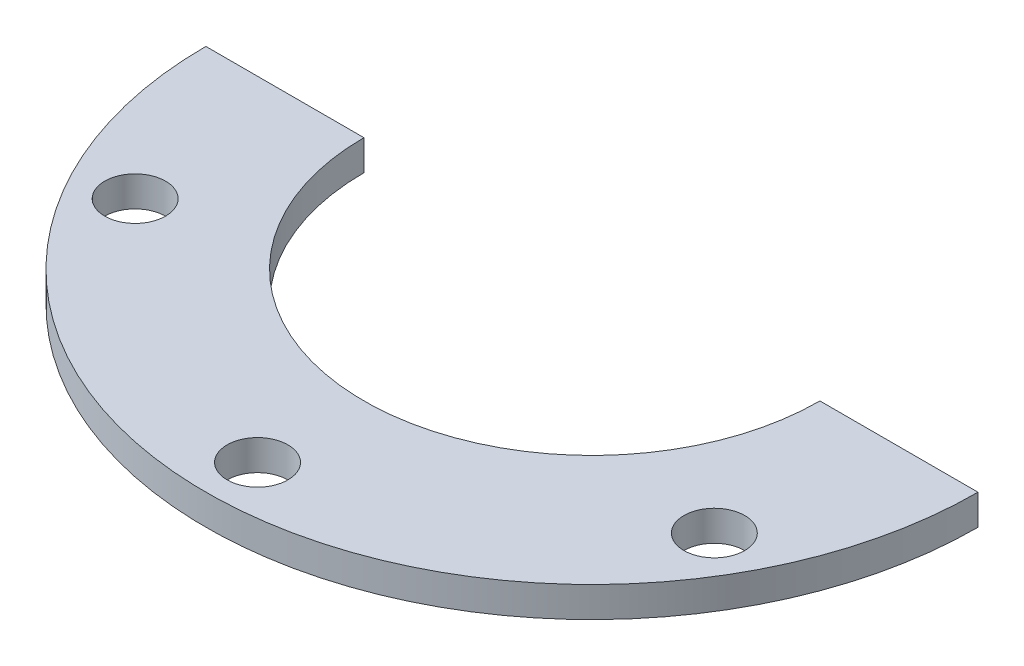
SolidWorks part; units mm, degrees
material "ABS"
ref_plane "Front Plane" through (0, 0, 0) normal (0, 0, 1) x (1, 0, 0)
ref_plane "Top Plane" through (0, 0, 0) normal (0, 1, 0) x (1, 0, 0)
ref_plane "Right Plane" through (0, 0, 0) normal (1, 0, 0) x (0, 0, -1)
sketch "Sketch1" plane through (0, 0, 0) normal (0, 1, 0) x (1, 0, 0)
  circle A0 centre (0, 0) radius 12.7
  dimension "D1" = 25.4
extrude "Boss-Extrude1" add sketch "Sketch1" along normal blind 1
sketch "Sketch19" plane through (0, 1, 0) normal (0, 1, 0) x (1, 0, 0)
  circle A0 centre (0, 11) radius 1
  circle A1 centre (9.5263, 5.5) radius 1
  circle A2 centre (9.5263, -5.5) radius 1
  circle A3 centre (0, -11) radius 1
  circle A4 centre (-9.5263, -5.5) radius 1
  circle A5 centre (-9.5263, 5.5) radius 1
  point P13 (0, 0)
  dimension "D1" = 2
  dimension "D2" = 11
  dimension "D3" = 6
extrude "Cut-Extrude1" cut sketch "Sketch19" against normal through all both and the other way through all
sketch "Sketch20" plane through (0, 1, 0) normal (0, 1, 0) x (1, 0, 0)
  circle A0 centre (0, 0) radius 7.5
  dimension "D1" = 15
extrude "Cut-Extrude2" cut sketch "Sketch20" against normal through all both and the other way through all
sketch "Sketch21" plane through (0, 0, 0) normal (0, 0, 1) x (1, 0, 0)
  line L1 (-36.7533, 32.3113) -> (29.1209, 32.3113)
  line L2 (-36.7533, 32.3113) -> (-36.7533, -19.668)
  line L3 (-36.7533, -19.668) -> (29.1209, -19.668)
  line L4 (29.1209, 32.3113) -> (29.1209, -19.668)
extrude "Cut-Extrude3" cut sketch "Sketch21" against normal through all
